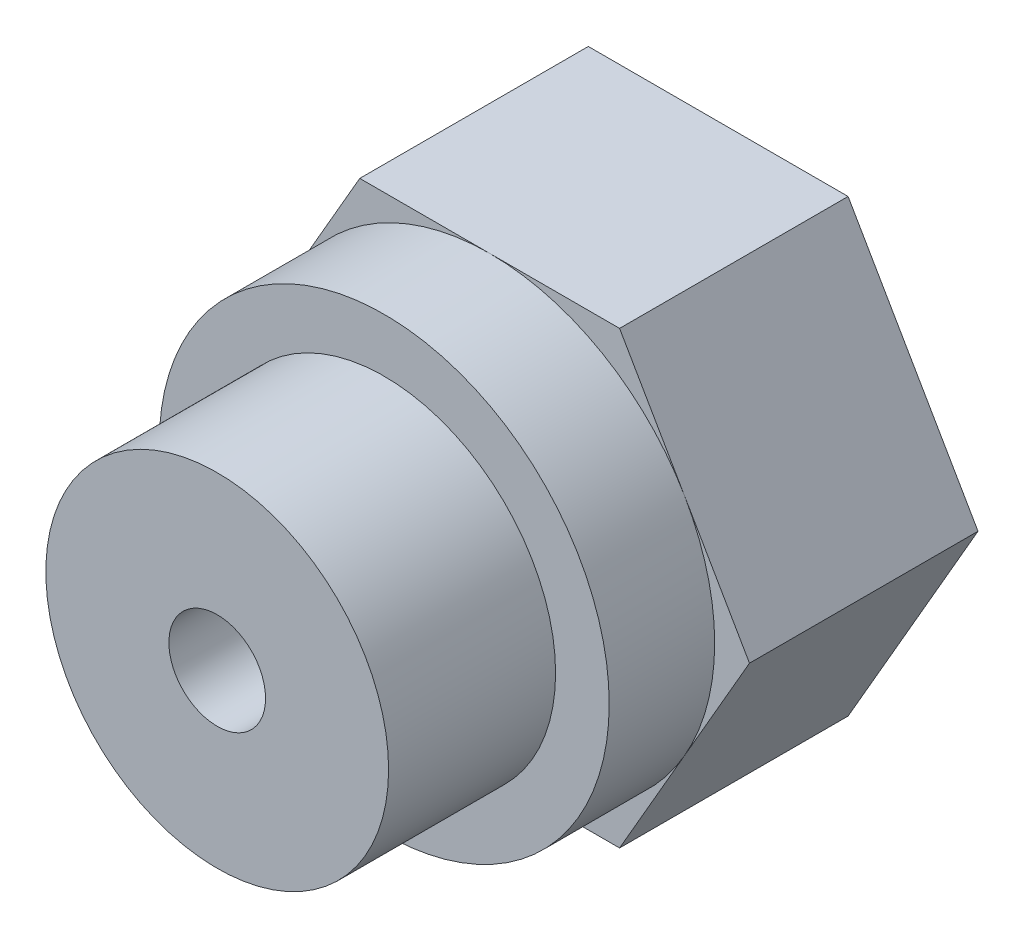
SolidWorks part; units mm, degrees
ref_plane "Front Plane" through (0, 0, 0) normal (0, 0, 1) x (1, 0, 0)
ref_plane "Top Plane" through (0, 0, 0) normal (0, 1, 0) x (1, 0, 0)
ref_plane "Right Plane" through (0, 0, 0) normal (1, 0, 0) x (0, 0, -1)
sketch "Sketch1" plane through (0, 0, 0) normal (0, 0, 1) x (1, 0, 0)
  line L1 (7.3901, 0) -> (3.695, 6.4)
  line L2 (3.695, 6.4) -> (-3.695, 6.4)
  line L3 (-3.695, 6.4) -> (-7.3901, 0)
  line L4 (-7.3901, 0) -> (-3.695, -6.4)
  line L5 (-3.695, -6.4) -> (3.695, -6.4)
  line L6 (3.695, -6.4) -> (7.3901, 0)
  circle A0 centre (0, 0) radius 6.4 construction
  dimension "D1" = 12.8
extrude "Boss-Extrude1" add sketch "Sketch1" along normal blind 6.5
sketch "Sketch2" plane through (0, 0, 6.5) normal (0, 0, 1) x (1, 0, 0)
  circle A0 centre (0, 0) radius 6.4
extrude "Boss-Extrude2" add sketch "Sketch2" along normal blind 3
sketch "Sketch3" plane through (0, 0, 0) normal (0, 0, -1) x (-1, 0, 0)
  circle A0 centre (0, 0) radius 4.2
  dimension "D1" = 8.4
extrude "Cut-Extrude1" cut sketch "Sketch3" against normal blind 7.5
sketch "Sketch5" plane through (0, 0, 9.5) normal (0, 0, 1) x (1, 0, 0)
  circle A0 centre (0, 0) radius 4.875
  dimension "D1" = 9.75
extrude "Boss-Extrude3" add sketch "Sketch5" along normal blind 4.75
sketch "Sketch6" plane through (0, 0, 14.25) normal (0, 0, 1) x (1, 0, 0)
  circle A0 centre (0, 0) radius 1.375
  dimension "D1" = 2.75
extrude "Cut-Extrude2" cut sketch "Sketch6" against normal through all
